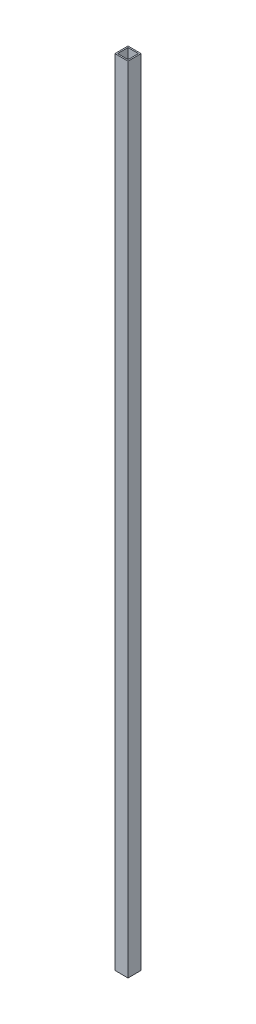
SolidWorks part; units mm, degrees
ref_plane "Спереди" through (0, 0, 0) normal (0, 0, 1) x (1, 0, 0)
ref_plane "Сверху" through (0, 0, 0) normal (0, 1, 0) x (1, 0, 0)
ref_plane "Справа" through (0, 0, 0) normal (1, 0, 0) x (0, 0, -1)
sketch "Эскиз1" plane through (0, 0, 0) normal (0, 1, 0) x (1, 0, 0)
  line L1 (-4, 4) -> (4, 4)
  line L2 (-4, 4) -> (-4, -4)
  line L3 (-4, -4) -> (4, -4)
  line L4 (4, 4) -> (4, -4)
  line L5 (-4, 4) -> (4, -4) construction
  line L6 (-4, -4) -> (4, 4) construction
  line L7 (-5, 5) -> (5, 5)
  line L8 (-5, 5) -> (-5, -5)
  line L9 (-5, -5) -> (5, -5)
  line L10 (5, 5) -> (5, -5)
  line L11 (-5, 5) -> (5, -5) construction
  line L12 (-5, -5) -> (5, 5) construction
  point P0 (0, 0)
  point P6 (0, 0)
  point P11 (-5, 0)
  dimension "D1" = 10
  dimension "D2" = 10
  dimension "D3" = 1
  dimension "D4" = 1
extrude "Бобышка-Вытянуть1" add sketch "Эскиз1" along normal blind 605
sketch "Эскиз2" plane through (-5, 0, 0) normal (-1, 0, 0) x (0, 0, 1)
  line L0 (-5, 0) -> (5, 0) construction
  line L1 (0, 17.5) -> (0, 0) construction
  line L2 (0, 605) -> (0, 587.5) construction
  line L3 (-5, 605) -> (5, 605) construction
  circle A0 centre (0, 17.5) radius 2.7
  circle A1 centre (0, 587.5) radius 2.7
  dimension "D2" = 5.4
  dimension "D4" = 5.4
  dimension "D1" = 17.5
  dimension "D3" = 17.5
extrude "Вырез-Вытянуть1" cut sketch "Эскиз2" against normal up to next
ref_plane "Плоскость1" through (0, 0, 0) normal (0, 0, 1) x (1, 0, 0)
